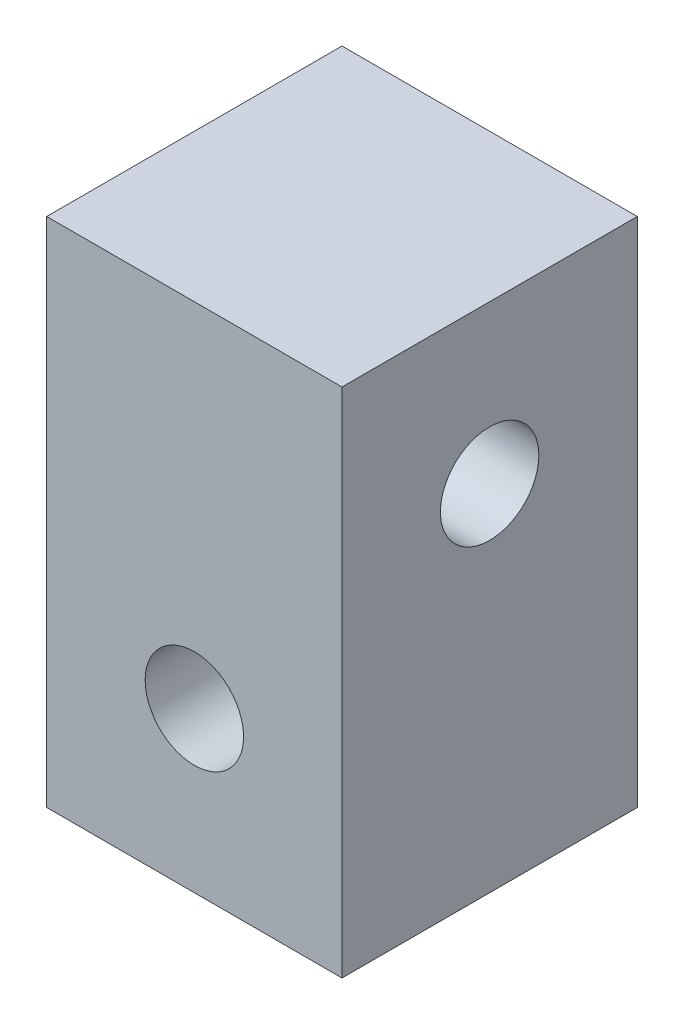
SolidWorks part; units mm, degrees
ref_plane "Front Plane" through (0, 0, 0) normal (0, 0, 1) x (1, 0, 0)
ref_plane "Top Plane" through (0, 0, 0) normal (0, 1, 0) x (1, 0, 0)
ref_plane "Right Plane" through (0, 0, 0) normal (1, 0, 0) x (0, 0, -1)
sketch "Sketch1" plane through (0, 0, 0) normal (0, 1, 0) x (1, 0, 0)
  line L1 (-3.75, -3.75) -> (3.75, -3.75)
  line L2 (-3.75, -3.75) -> (-3.75, 3.75)
  line L3 (-3.75, 3.75) -> (3.75, 3.75)
  line L4 (3.75, -3.75) -> (3.75, 3.75)
  line L5 (-3.75, -3.75) -> (3.75, 3.75) construction
  line L6 (-3.75, 3.75) -> (3.75, -3.75) construction
  point P0 (0, 0)
  dimension "D1" = 7.5
  dimension "D2" = 7.5
extrude "Boss-Extrude1" add sketch "Sketch1" along normal blind 13
sketch "Sketch2" plane through (0, 0, -3.75) normal (0, 0, -1) x (-1, 0, 0)
  circle A0 centre (0, 4.0531) radius 1.25
  dimension "D1" = 2.5
extrude "Cut-Extrude1" cut sketch "Sketch2" against normal blind 10
sketch "Sketch3" plane through (3.75, 0, 0) normal (1, 0, 0) x (0, 0, -1)
  line L0 (-3.75, 0) -> (3.75, 0) construction
  circle A0 centre (0, 9) radius 1.25
  dimension "D1" = 2.5
  dimension "D2" = 9
extrude "Cut-Extrude2" cut sketch "Sketch3" against normal blind 10
